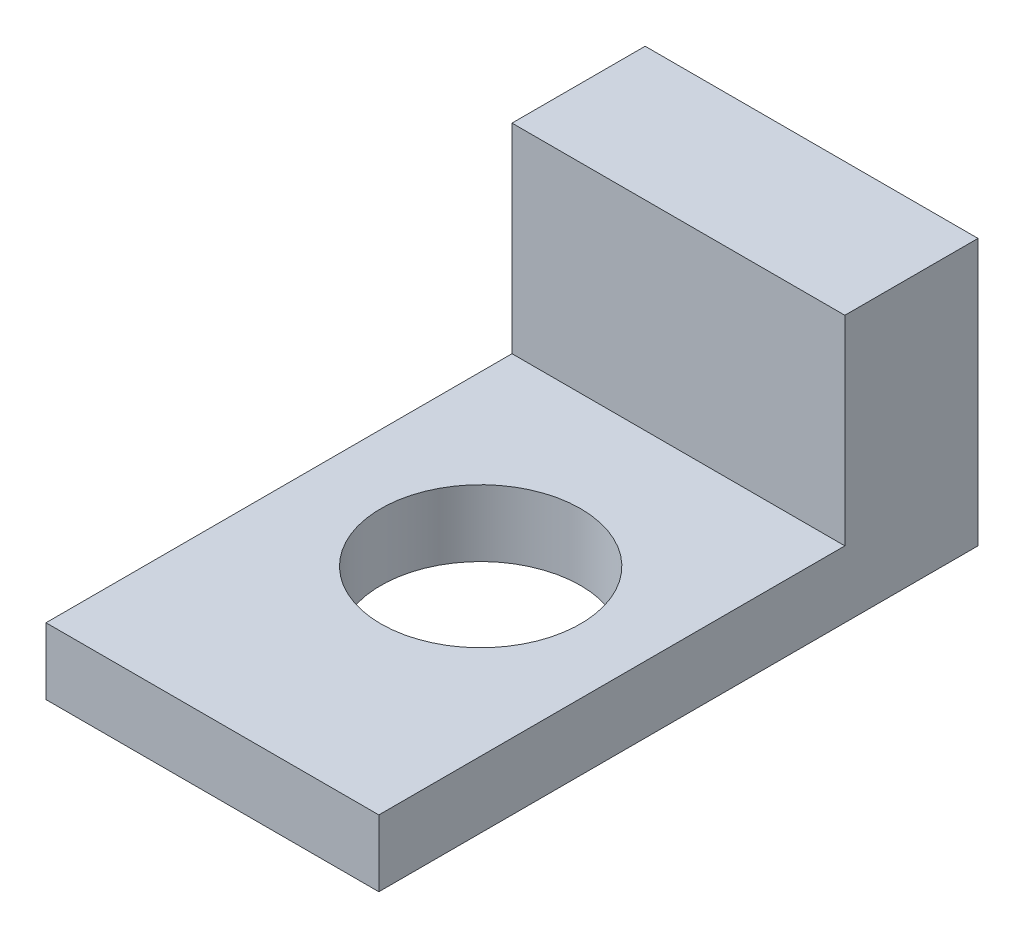
SolidWorks part; units mm, degrees
ref_plane "Front Plane" through (0, 0, 0) normal (0, 0, 1) x (1, 0, 0)
ref_plane "Top Plane" through (0, 0, 0) normal (0, 1, 0) x (1, 0, 0)
ref_plane "Right Plane" through (0, 0, 0) normal (1, 0, 0) x (0, 0, -1)
sketch "Sketch1" plane through (0, 0, 0) normal (0, 0, 1) x (1, 0, 0)
  line L1 (0, 0) -> (50, 0)
  line L2 (0, 0) -> (0, -10)
  line L3 (0, -10) -> (50, -10)
  line L4 (50, 0) -> (50, -10)
  dimension "D1" = 50
  dimension "D2" = 10
extrude "Boss-Extrude1" add sketch "Sketch1" along normal blind 90
sketch "Sketch2" plane through (0, 0, 0) normal (0, 1, 0) x (1, 0, 0)
  line L0 (50, -90) -> (50, 0) construction
  line L1 (0, 0) -> (50, 0)
  line L2 (0, 0) -> (0, -20)
  line L3 (0, -20) -> (50, -20)
  line L4 (50, 0) -> (50, -20)
  dimension "D1" = 20
extrude "Boss-Extrude2" add sketch "Sketch2" along normal blind 30
sketch "Sketch3" plane through (0, 0, 0) normal (0, 1, 0) x (1, 0, 0)
  line L0 (50, 0) -> (0, 0) construction
  circle A0 centre (25.2949, -50) radius 15.0006
  dimension "D1" = 30.0012
  dimension "D2" = 50
extrude "Cut-Extrude1" cut sketch "Sketch3" against normal through all
